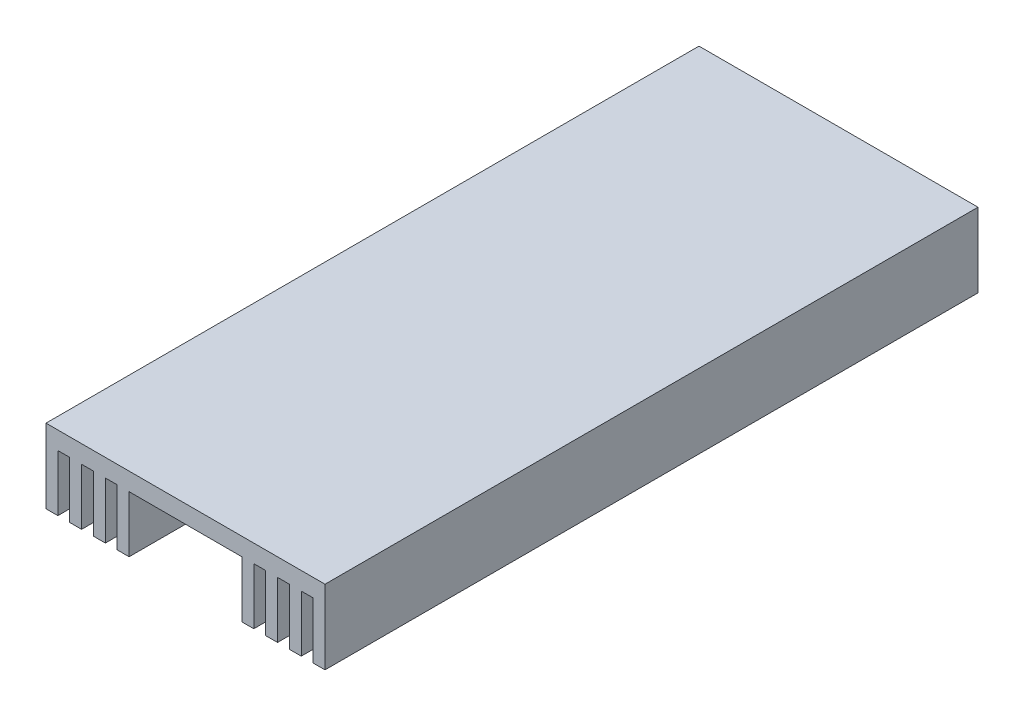
SolidWorks part; units mm, degrees
material "1060 Alloy"
ref_plane "Front Plane" through (0, 0, 0) normal (0, 0, 1) x (1, 0, 0)
ref_plane "Top Plane" through (0, 0, 0) normal (0, 1, 0) x (1, 0, 0)
ref_plane "Right Plane" through (0, 0, 0) normal (1, 0, 0) x (0, 0, -1)
sketch "Sketch1" plane through (0, 0, 0) normal (0, 0, 1) x (1, 0, 0)
  line L0 (0, 0) -> (0, 12.5)
  line L1 (0, 12.5) -> (47, 12.5)
  line L2 (47, 12.5) -> (47, 0)
  line L3 (0, 0) -> (2, 0)
  line L4 (2, 0) -> (2, 9.5)
  line L5 (2, 9.5) -> (4, 9.5)
  line L6 (4, 9.5) -> (4, 0)
  line L7 (4, 0) -> (6, 0)
  line L8 (6, 0) -> (6, 9.5)
  line L9 (6, 9.5) -> (8, 9.5)
  line L10 (8, 9.5) -> (8, 0)
  line L11 (8, 0) -> (10, 0)
  line L12 (10, 0) -> (10, 9.5)
  line L13 (10, 9.5) -> (12, 9.5)
  line L14 (12, 9.5) -> (12, 0)
  line L15 (12, 0) -> (14, 0)
  line L16 (14, 0) -> (14, 9.5)
  line L17 (14, 9.5) -> (33, 9.5)
  line L18 (23.5, 12.5) -> (23.5, 0) construction
  line L19 (33, 0) -> (33, 9.5)
  line L20 (35, 0) -> (33, 0)
  line L21 (35, 9.5) -> (35, 0)
  line L22 (37, 9.5) -> (35, 9.5)
  line L23 (37, 0) -> (37, 9.5)
  line L24 (39, 0) -> (37, 0)
  line L25 (39, 9.5) -> (39, 0)
  line L26 (41, 9.5) -> (39, 9.5)
  line L27 (41, 0) -> (41, 9.5)
  line L28 (43, 0) -> (41, 0)
  line L29 (43, 9.5) -> (43, 0)
  line L30 (45, 9.5) -> (43, 9.5)
  line L31 (45, 0) -> (45, 9.5)
  line L32 (47, 0) -> (45, 0)
  line L33 (47, 0) -> (47, 12.5)
  point P24 (23.5, 9.5)
  dimension "D1" = 12.5
  dimension "D2" = 47
  dimension "D4" = 3
  dimension "D5" = 2
  dimension "D6" = 2
  dimension "D7" = 2
  dimension "D8" = 2
  dimension "D9" = 2
  dimension "D10" = 2
  dimension "D11" = 2
  dimension "D12" = 3
  dimension "D13" = 2
  dimension "D14" = 3
  dimension "D15" = 3
extrude "Boss-Extrude1" add sketch "Sketch1" along normal blind 110 contours L18 L1 L0 L3 L4 L5 L6 L7 L8 L9 L10 L11 L12 L13 L14 L15 L16 L17 | L1 L18 L17 L19 L20 L21 L22 L23 L24 L25 L26 L27 L28 L29 L30 L31 L32 L2
